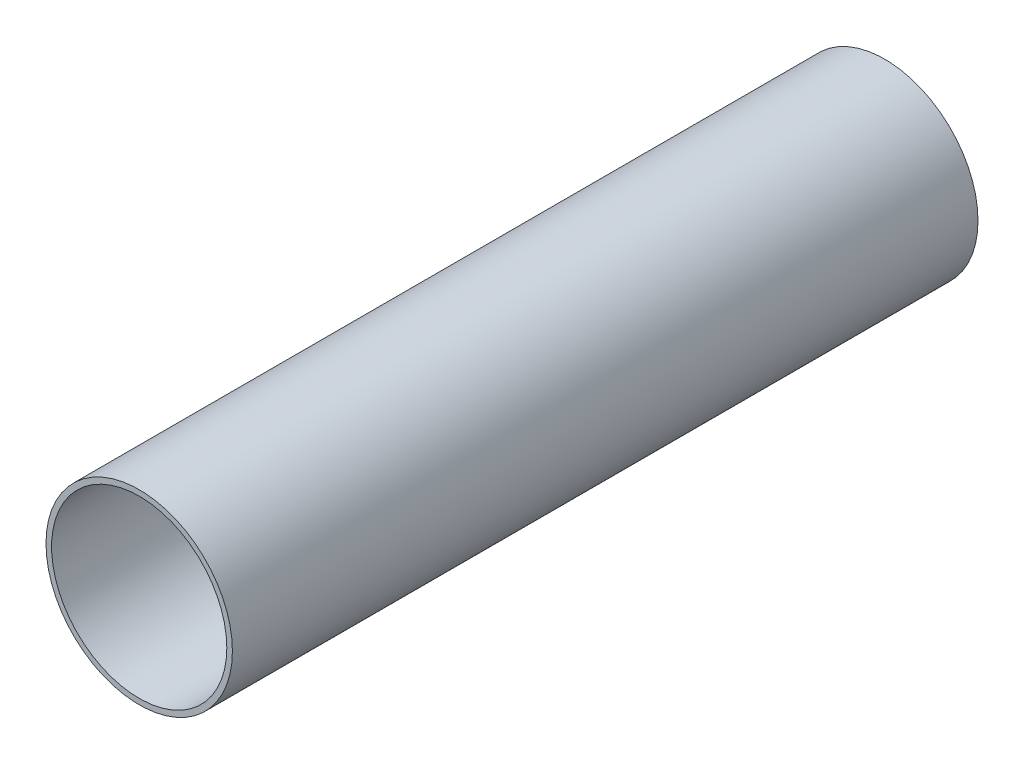
SolidWorks part; units mm, degrees
ref_plane "Front Plane" through (0, 0, 0) normal (0, 0, 1) x (1, 0, 0)
ref_plane "Top Plane" through (0, 0, 0) normal (0, 1, 0) x (1, 0, 0)
ref_plane "Right Plane" through (0, 0, 0) normal (1, 0, 0) x (0, 0, -1)
sketch "Sketch1" plane through (0, 0, 0) normal (0, 0, 1) x (1, 0, 0)
  circle A0 centre (0, 0) radius 50
  circle A1 centre (0, 0) radius 47
  dimension "D1" = 100
  dimension "D2" = 3
extrude "Boss-Extrude1" add sketch "Sketch1" along normal blind 400
